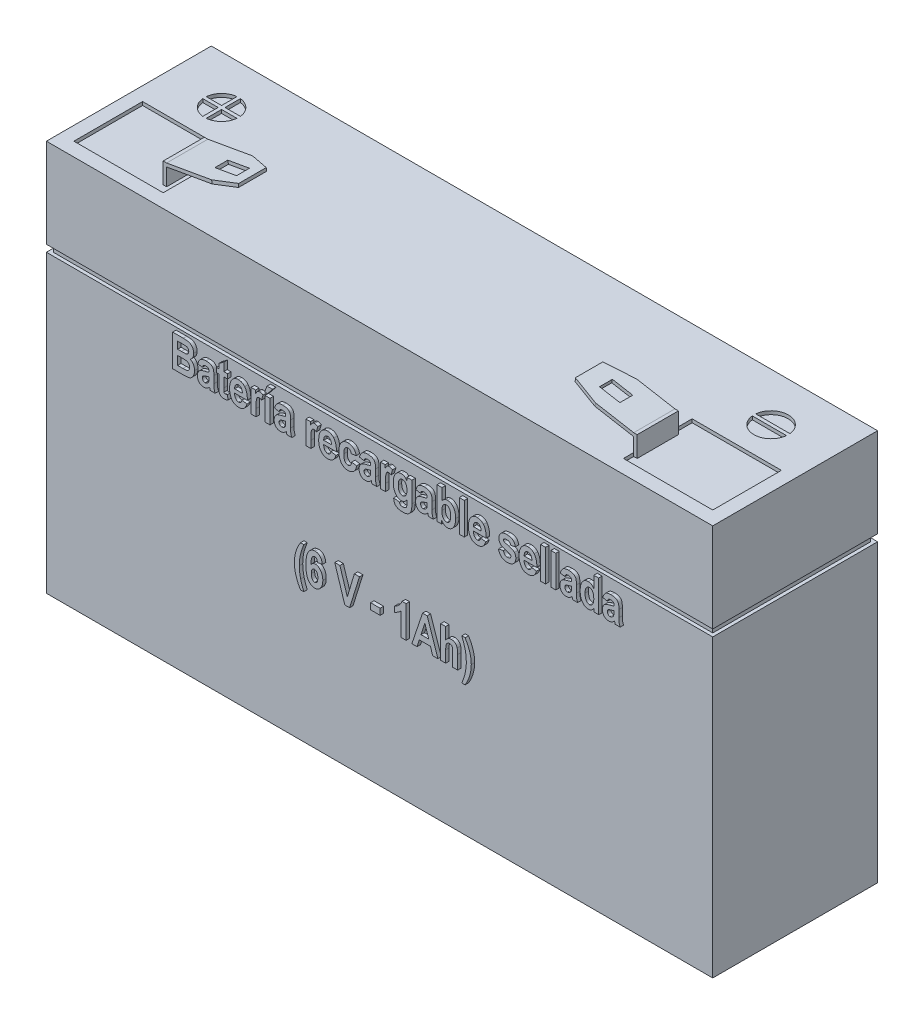
SolidWorks part; units mm, degrees
other "Marca1"
sketch "Croquis9"
ref_plane "Alzado" through (0, 0, 0) normal (0, 0, 1) x (1, 0, 0)
ref_plane "Planta" through (0, 0, 0) normal (0, 1, 0) x (1, 0, 0)
ref_plane "Vista lateral" through (0, 0, 0) normal (1, 0, 0) x (0, 0, -1)
sketch "Croquis1" plane through (0, 0, 0) normal (0, 0, 1) x (1, 0, 0)
  line L1 (-48.5, -28.5) -> (48.5, -28.5)
  line L2 (-48.5, -28.5) -> (-48.5, 28.5)
  line L3 (-48.5, 28.5) -> (48.5, 28.5)
  line L4 (48.5, -28.5) -> (48.5, 28.5)
  line L5 (-48.5, -28.5) -> (48.5, 28.5) construction
  line L6 (-48.5, 28.5) -> (48.5, -28.5) construction
  point P0 (0, 0)
  dimension "D1" = 97
  dimension "D2" = 57
extrude "Saliente-Extruir1" add sketch "Croquis1" along normal mid plane 24
sketch "Croquis2" plane through (48.5, 0, 0) normal (1, 0, 0) x (0, 0, -1)
  line L0 (-12, 15) -> (12, 15) construction
  line L1 (-12, -28.5) -> (-12, 28.5) construction
  line L2 (12, -28.5) -> (12, 28.5) construction
  line L3 (-12, 28.5) -> (12, 28.5) construction
  line L5 (-11.5, 14.5) -> (-12.5, 14.5)
  line L6 (-11.5, 14.5) -> (-11.5, 15.5)
  line L7 (-11.5, 15.5) -> (-12.5, 15.5)
  line L8 (-12.5, 14.5) -> (-12.5, 15.5)
  line L9 (-11.5, 14.5) -> (-12.5, 15.5) construction
  line L10 (-11.5, 15.5) -> (-12.5, 14.5) construction
  dimension "D1" = 13.5
  dimension "D2" = 1
  dimension "D3" = 1
extrude "Cortar-Extruir1" cut sketch "Croquis2" against normal up to next
ref_plane "Plano1" through (0, 0, 0) normal (0, 0, 1) x (1, 0, 0)
mirror "Simetría2" about plane through (0, 0, 0) normal (0, 0, 1) of "Cortar-Extruir1"
ref_plane "Plano2" through (0, 0, 0) normal (1, 0, 0) x (0, 0, -1)
sketch "Croquis4" plane through (0, 0, 12) normal (0, 0, 1) x (1, 0, 0)
  line L0 (48.5, 14.5) -> (48.5, 15.5) construction
  line L1 (48, 14.5) -> (49, 14.5)
  line L2 (48, 14.5) -> (48, 15.5)
  line L3 (48, 15.5) -> (49, 15.5)
  line L4 (49, 14.5) -> (49, 15.5)
  line L5 (48, 14.5) -> (49, 15.5) construction
  line L6 (48, 15.5) -> (49, 14.5) construction
  point P0 (48.5, 15)
  dimension "D1" = 1
  dimension "D2" = 1
extrude "Cortar-Extruir2" cut sketch "Croquis4" against normal up to next
mirror "Simetría3" about plane through (0, 0, 0) normal (1, 0, 0) of "Cortar-Extruir2"
sketch "Croquis5" plane through (0, 28.5, 0) normal (0, 1, 0) x (1, 0, 0)
  line L0 (-48.5, -12) -> (-48.5, 12) construction
  line L2 (-46.5, -10) -> (46.5, -10) construction
  line L4 (-46.5, -10) -> (-46.5, 10) construction
  line L5 (-46.5, 10) -> (46.5, 10) construction
  line L6 (46.5, -10) -> (46.5, 10) construction
  line L7 (-46.5, -10) -> (46.5, 10) construction
  line L8 (-46.5, 10) -> (46.5, -10) construction
  line L10 (48.5, 12) -> (-48.5, 12) construction
  line L11 (-52.0538, 0) -> (55.1173, 0) construction
  line L12 (-46.5, 10) -> (-33.5, 10)
  line L13 (-46.5, 10) -> (-46.5, -10)
  line L14 (-46.5, -10) -> (-33.5, -10)
  line L15 (-33.5, 10) -> (-33.5, -10)
  line L16 (46.5, 10) -> (33.5, 10)
  line L17 (46.5, 10) -> (46.5, -10)
  line L18 (46.5, -10) -> (33.5, -10)
  line L19 (33.5, 10) -> (33.5, -10)
  line L20 (-33.5, 0) -> (-46.5, 10) construction
  line L21 (33.5, 0) -> (46.5, 10) construction
  line L22 (-46.5, 0) -> (-33.5, 0)
  line L23 (-42.4875, 4.75) -> (-37.5125, 4.75)
  line L25 (-42.4875, 5.25) -> (-37.5125, 5.25)
  line L27 (-42.4914, 4.7925) -> (-37.5086, 5.2075) construction
  line L28 (-42.4914, 5.2075) -> (-37.5086, 4.7925) construction
  line L30 (-40.25, 2.5125) -> (-40.25, 7.4875)
  line L32 (-39.75, 2.5125) -> (-39.75, 7.4875)
  line L33 (-40.2077, 2.5086) -> (-39.7923, 7.4914) construction
  line L34 (-40.2077, 7.4914) -> (-39.7923, 2.5086) construction
  line L35 (37.5125, 4.75) -> (42.4875, 4.75)
  line L37 (37.5125, 5.25) -> (42.4875, 5.25)
  line L39 (37.5106, 4.7698) -> (42.4894, 5.2302) construction
  line L40 (37.5106, 5.2302) -> (42.4894, 4.7698) construction
  line L41 (33.5, 0) -> (46.5, 0)
  circle A0 centre (-40, 5) radius 2.5
  circle A1 centre (40, 5) radius 2.5
  point P0 (0, 0)
  dimension "D5" = 5
  dimension "D6" = 5
  dimension "D1" = 2
  dimension "D2" = 2
  dimension "D3" = 13
  dimension "D4" = 13
  dimension "D7" = 0.5
extrude "Cortar-Extruir3" cut sketch "Croquis5" against normal blind 0.5 contours L22 L13 L14 L15 | L41 L19 L18 L17 | L35 A1 | L37 A1 | L30 A0 L25 | L25 A0 L32 | L23 A0 L30 | L32 A0 L23
ref_plane "Plano3" through (0, 0, 9) normal (0, 0, 1) x (1, 0, 0)
sketch "Croquis6" plane through (0, 0, 9) normal (0, 0, 1) x (1, 0, 0)
  line L0 (-34.5, 28.5) -> (-34.5, 52.0771) construction
  line L1 (48.5, 28.5) -> (-48.5, 28.5) construction
  line L2 (-48.5, 28.5) -> (-48.5, 15.5) construction
  line L3 (0, -28.5) -> (0, 84.6398) construction
  line L5 (-34, 31) -> (-24.5, 32.6751)
  line L6 (-34.5, 28.5) -> (-34, 28.5)
  line L7 (-34.5, 28.5) -> (-34.5, 31.5)
  line L8 (-34.5, 31.5) -> (-34, 31.5)
  line L9 (-34, 28.5) -> (-34, 31)
  line L10 (-34, 31.5) -> (-24.5, 33.1751)
  line L11 (-24.5, 33.1751) -> (-24.5, 32.6751)
  line L12 (-48.5, -28.5) -> (48.5, -28.5) construction
  line L13 (34.5, 28.5) -> (34, 28.5)
  line L14 (34, 28.5) -> (34, 31)
  line L15 (34.5, 28.5) -> (34.5, 31.5)
  line L16 (34.5, 31.5) -> (34, 31.5)
  line L17 (24.5, 33.1751) -> (24.5, 32.6751)
  line L18 (34, 31) -> (24.5, 32.6751)
  line L19 (34, 31.5) -> (24.5, 33.1751)
  dimension "D1" = 14
  dimension "D3" = 3
  dimension "D4" = 0.5
  dimension "D5" = 0.5
  dimension "D6" = 80
  dimension "D7" = 10
  dimension "D8" = 0.5
extrude "Saliente-Extruir2" add sketch "Croquis6" against normal blind 6 separate body
sketch "Croquis7" plane through (-6.412, 36.3645, 0) normal (-0.1736, 0.9848, 0) x (0.9848, 0.1736, 0)
  line L0 (-21.367, 0.8123) -> (-21.367, -10.9274) construction
  line L1 (-18.367, -3) -> (-18.367, -9) construction
  line L2 (-18.367, -6) -> (-25.951, -6) construction
  line L3 (-21.367, -9) -> (-18.367, -8)
  line L4 (-22.9689, -6.9425) -> (-19.765, -6.9425)
  line L5 (-22.9689, -6.9425) -> (-22.9689, -5.0575)
  line L6 (-22.9689, -5.0575) -> (-19.765, -5.0575)
  line L7 (-19.765, -6.9425) -> (-19.765, -5.0575)
  line L8 (-22.9689, -6.9425) -> (-19.765, -5.0575) construction
  line L9 (-22.9689, -5.0575) -> (-19.765, -6.9425) construction
  line L10 (-18.367, -9) -> (-28.0135, -9) construction
  line L11 (-21.367, -3) -> (-18.367, -4)
  line L12 (-18.367, -3) -> (-28.0135, -3) construction
  line L13 (-21.367, -9) -> (-18.367, -9)
  line L14 (-18.367, -9) -> (-18.367, -8)
  line L15 (-18.367, -4) -> (-18.367, -3)
  line L16 (-18.367, -3) -> (-21.367, -3)
  line L17 (0, 23.3324) -> (0, -23.3287) construction
  point P6 (-21.367, -6)
  dimension "D1" = 3
  dimension "D2" = 2
  dimension "D3" = 2
extrude "Cortar-Extruir4" cut sketch "Croquis7" against normal up to next (0.4924 mm away) contours L5 L4 L7 L6 | L14 L3 L13 | L16 L11 L15
sketch "Croquis8" plane through (6.412, 36.3645, 0) normal (0.1736, 0.9848, 0) x (0.9848, -0.1736, 0)
  line L0 (22.367, 1.7713) -> (22.367, -19.7713) construction
  line L1 (18.367, -3) -> (18.367, -9) construction
  line L2 (18.367, -6) -> (26.9491, -6) construction
  line L3 (18.367, -8) -> (22.367, -9)
  line L4 (23.8705, -6.9369) -> (20.8635, -6.9369)
  line L5 (23.8705, -6.9369) -> (23.8705, -5.0631)
  line L6 (23.8705, -5.0631) -> (20.8635, -5.0631)
  line L7 (20.8635, -6.9369) -> (20.8635, -5.0631)
  line L8 (23.8705, -6.9369) -> (20.8635, -5.0631) construction
  line L9 (23.8705, -5.0631) -> (20.8635, -6.9369) construction
  line L10 (18.367, -4) -> (22.367, -3)
  line L11 (18.367, -4) -> (18.367, -3)
  line L12 (18.367, -3) -> (22.367, -3)
  line L13 (18.367, -8) -> (18.367, -9)
  line L14 (28.0135, -9) -> (18.367, -9) construction
  line L15 (18.367, -9) -> (22.367, -9)
  line L16 (28.0135, -3) -> (18.367, -3) construction
  point P6 (22.367, -6)
  dimension "D1" = 4
  dimension "D2" = 2
  dimension "D3" = 2
extrude "Cortar-Extruir5" cut sketch "Croquis8" against normal up to next (0.4924 mm away)
sketch "Croquis10" plane through (0, 0, 12) normal (0, 0, 1) x (1, 0, 0)
  line L0 (-49.0892, 9.5) -> (50.9108, 9.5) construction
  line L1 (-48, 14.5) -> (48, 14.5) construction
  text T0 "<b>Batería recargable sellada</b>\r\n\r\n<b>(6 V - 1Ah)</b>" font "Arial Narrow" height in points 18
  dimension "D1" = 100
  dimension "D2" = 50
  dimension "D3" = 5
extrude "Saliente-Extruir4" add sketch "Croquis10" along normal blind 0.5
